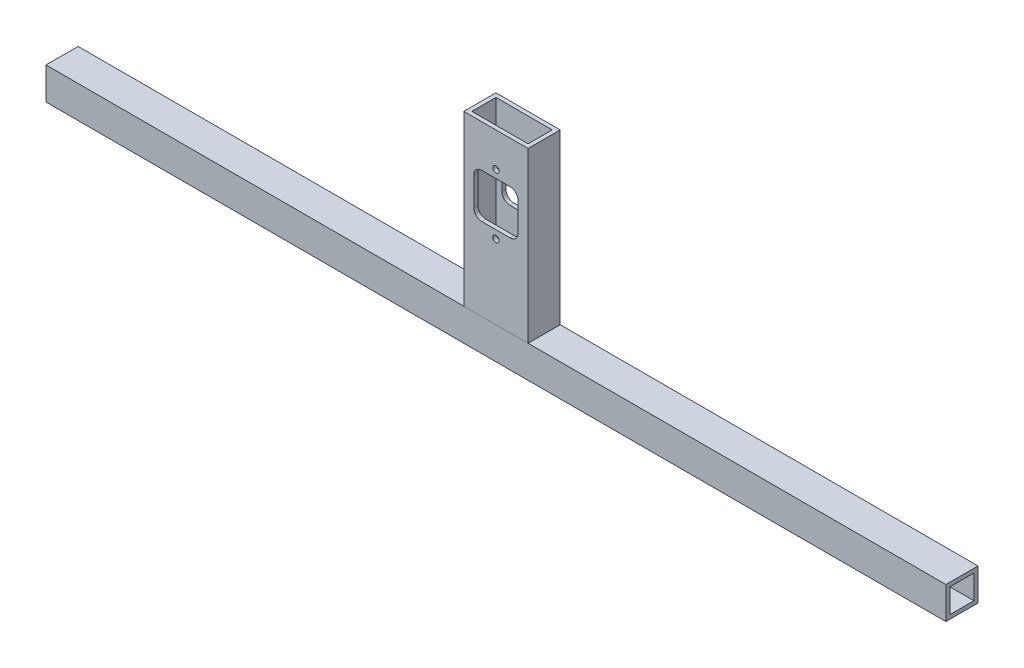
SolidWorks part; units mm, degrees
ref_plane "Alzado" through (0, 0, 0) normal (0, 0, 1) x (1, 0, 0)
ref_plane "Planta" through (0, 0, 0) normal (0, 1, 0) x (1, 0, 0)
ref_plane "Vista lateral" through (0, 0, 0) normal (1, 0, 0) x (0, 0, -1)
sketch "Croquis1" plane through (0, 0, 0) normal (0, 0, 1) x (1, 0, 0)
  line L0 (0, 0) -> (0, 68.072) construction
  line L5 (-355.6, -68.072) -> (355.6, -68.072)
  line L6 (-355.6, -68.072) -> (-355.6, 68.072)
  line L11 (-355.6, 68.072) -> (355.6, 68.072)
  line L13 (-355.6, -68.072) -> (355.6, 68.072) construction
  line L14 (-355.6, 68.072) -> (355.6, -68.072) construction
  line L15 (-355.6, 144.272) -> (-355.6, 17.272)
  line L20 (355.6, 68.072) -> (355.6, -68.072)
  line L21 (355.6, 17.272) -> (374.65, 17.272)
  line L22 (374.65, 17.272) -> (406.4, 17.272)
  line L23 (-374.65, 144.272) -> (-355.6, 144.272)
  line L24 (355.6, 17.272) -> (355.6, 68.072)
  line L25 (374.65, 144.272) -> (374.65, 17.272) construction
  line L26 (438.15, 49.022) -> (438.15, 112.522)
  line L27 (406.4, 144.272) -> (374.65, 144.272)
  line L28 (374.65, 144.272) -> (355.6, 144.272)
  line L29 (355.6, 144.272) -> (355.6, 17.272)
  line L30 (-406.4, 144.272) -> (-374.65, 144.272)
  line L31 (-438.15, 49.022) -> (-438.15, 112.522)
  line L32 (-355.6, 17.272) -> (-355.6, 68.072)
  line L33 (-374.65, 17.272) -> (-406.4, 17.272)
  line L34 (-355.6, 17.272) -> (-374.65, 17.272)
  arc A2 (406.4, 17.272) -> (438.15, 49.022) centre (406.4, 49.022) ccw
  arc A3 (438.15, 112.522) -> (406.4, 144.272) centre (406.4, 112.522) ccw
  arc A4 (-438.15, 112.522) -> (-406.4, 144.272) centre (-406.4, 112.522) cw
  arc A5 (-406.4, 17.272) -> (-438.15, 49.022) centre (-406.4, 49.022) cw
  point P0 (0, 0)
  point P29 (0, 0)
  dimension "D4" = 31.75
  dimension "D3" = 63.5
  dimension "D5" = 19.05
  dimension "D1" = 136.144
  dimension "D2" = 711.2
  dimension "D6" = 76.2
  dimension "D7" = 127
sketch "Croquis2" plane through (0, 0, 0) normal (0, 0, 1) x (1, 0, 0)
  line L0 (355.6, -68.072) -> (514.35, -68.072) construction
  line L1 (514.35, -68.072) -> (514.35, 620.903)
  line L3 (438.15, 49.022) -> (438.15, 112.522) construction
  line L4 (514.35, 620.903) -> (1193.1608, 1096.2115)
  line L5 (514.35, 620.903) -> (1193.1608, 620.903) construction
  point P6 (0, 0)
  dimension "D1" = 76.2
  dimension "D2" = 35
  dimension "D3" = 828.675
  dimension "D4" = 688.975
sketch "Croquis3" plane through (0, 0, 0) normal (0, 0, 1) x (1, 0, 0)
  line L0 (0, 68.072) -> (0, 176.022)
  line L1 (-355.6, 68.072) -> (355.6, 68.072) construction
  line L2 (0, 176.022) -> (-438.15, 176.022) construction
  line L3 (-438.15, 176.022) -> (-666.75, 176.022) construction
  line L4 (74.168, 201.422) -> (-438.15, 201.422)
  line L5 (74.168, 150.622) -> (-438.15, 150.622)
  line L6 (74.168, 150.622) -> (74.168, 201.422)
  line L7 (-438.15, 150.622) -> (-438.15, 201.422)
  line L8 (74.168, 176.022) -> (-438.15, 176.022) construction
  line L9 (-666.75, -23.622) -> (-355.6, -23.622) construction
  line L10 (-355.6, -68.072) -> (355.6, -68.072) construction
  line L15 (-473.6284, -45.0532) -> (-526.9684, 257.302)
  line L16 (-526.9684, 257.302) -> (-549.8284, 257.302)
  line L17 (-549.8284, 257.302) -> (-549.8284, -45.0532) construction
  line L18 (-549.8284, -45.0532) -> (-473.6284, -45.0532) construction
  line L20 (-355.6, -68.072) -> (-355.6, 68.072) construction
  line L23 (-612.8204, 5.7468) -> (-612.8204, -19.6532) construction
  line L26 (-562.0204, 5.7468) -> (-663.6204, 5.7468)
  line L29 (-562.0204, 5.7468) -> (-562.0204, -19.6532)
  line L32 (-562.0204, -19.6532) -> (-663.6204, -19.6532)
  line L35 (-663.6204, 5.7468) -> (-663.6204, -19.6532)
  line L36 (-612.8204, 346.2972) -> (-612.8204, 371.6972) construction
  line L37 (-663.6204, 346.2972) -> (-663.6204, 371.6972)
  line L38 (-562.0204, 371.6972) -> (-663.6204, 371.6972)
  line L39 (-562.0204, 346.2972) -> (-562.0204, 371.6972)
  line L40 (-562.0204, 346.2972) -> (-663.6204, 346.2972)
  line L41 (-57.6798, 122.9269) -> (186.5051, 573.3083)
  line L42 (-57.6798, 122.9269) -> (-13.0212, 98.7142)
  line L43 (186.5051, 573.3083) -> (231.1637, 549.0956)
  line L44 (-13.0212, 98.7142) -> (231.1637, 549.0956)
  line L45 (208.8344, 561.202) -> (-35.3505, 110.8205) construction
  line L46 (208.8344, 561.202) -> (316.2998, 759.4143) construction
  line L47 (417.5643, 588.9393) -> (439.8936, 576.8329)
  line L48 (417.5643, 588.9393) -> (465.9897, 678.2564)
  line L49 (439.8936, 576.8329) -> (488.319, 666.15)
  line L50 (465.9897, 678.2564) -> (488.319, 666.15)
  line L51 (-562.0204, 5.7468) -> (-438.15, 5.7468) construction
  line L52 (417.5643, 588.9393) -> (358.5243, 480.0441) construction
  line L53 (231.1637, 549.0956) -> (358.5243, 480.0441) construction
  line L54 (-438.15, 150.622) -> (-438.15, 5.7468) construction
  line L55 (316.2998, 759.4143) -> (488.319, 666.15) construction
  circle A0 centre (0, 176.022) radius 74.168
  arc A17 (-438.15, 49.022) -> (-406.4, 17.272) centre (-406.4, 49.022) ccw construction
  dimension "D1" = 148.336
  dimension "D11" = 50.8
  dimension "D2" = 228.6
  dimension "D5" = 44.45
  dimension "D6" = 25.4
  dimension "D7" = 101.6
  dimension "D8" = 22.86
  dimension "D9" = 76.2
  dimension "D10" = 23.0188
  dimension "D12" = 325.374
  dimension "D14" = 107.95
  dimension "D13" = 25.4
  dimension "D15" = 62.992
  dimension "D16" = 44.45
  dimension "D3" = 25.4
  dimension "D4" = 25.4
sketch "Croquis4" plane through (0, 0, 0) normal (0, 0, 1) x (1, 0, 0)
  line L0 (-355.6, 144.272) -> (-355.6, 17.272) construction
  line L1 (355.6, 68.072) -> (-355.6, 68.072)
  line L2 (355.6, 68.072) -> (355.6, 93.472)
  line L3 (355.6, 93.472) -> (-355.6, 93.472)
  line L4 (-355.6, 68.072) -> (-355.6, 93.472)
  line L5 (0, 226.822) -> (0, 93.472) construction
  line L6 (25.4, 93.472) -> (-25.4, 93.472)
  line L7 (25.4, 93.472) -> (25.4, 226.822)
  line L8 (25.4, 226.822) -> (-25.4, 226.822)
  line L9 (-25.4, 93.472) -> (-25.4, 226.822)
  line L10 (0, 68.072) -> (0, 176.022) construction
  line L11 (74.168, 201.422) -> (-438.15, 201.422) construction
  circle A0 centre (175.4299, 126.647) radius 30
  circle A1 centre (175.4299, 126.647) radius 7.62
  circle A2 centre (123.7021, 153.797) radius 50.8
  point P22 (117.7259, 152.1718)
  point P23 (123.0145, 153.797)
  point P25 (123.7021, 153.797)
  dimension "D1" = 60
  dimension "D2" = 15.24
  dimension "D4" = 101.6
  dimension "D3" = 25.4
  dimension "D5" = 50.8
  dimension "D6" = 25.4
  dimension "D7" = 3.175
  dimension "D8" = 9.525
sketch "Croquis5" plane through (0, 0, 0) normal (0, 0, 1) x (1, 0, 0)
  line L1 (-355.6, 93.472) -> (355.6, 93.472)
  line L2 (-355.6, 93.472) -> (-355.6, 68.072)
  line L3 (-355.6, 68.072) -> (355.6, 68.072)
  line L4 (355.6, 93.472) -> (355.6, 68.072)
extrude "Saliente-Extruir1" add sketch "Croquis5" against normal blind 25.4
sketch "Croquis6" plane through (0, 0, 0) normal (0, 0, 1) x (1, 0, 0)
  line L1 (-25.4, 226.822) -> (25.4, 226.822)
  line L2 (-25.4, 226.822) -> (-25.4, 93.472)
  line L3 (-25.4, 93.472) -> (25.4, 93.472)
  line L4 (25.4, 226.822) -> (25.4, 93.472)
extrude "Saliente-Extruir2" add sketch "Croquis6" against normal blind 25.4 separate body
shell "Vaciado1" thickness 3.175
shell "Vaciado2" thickness 3.175
sketch "Croquis7" plane through (0, 0, 0) normal (0, 0, 1) x (1, 0, 0)
  line L0 (0, 152.2095) -> (0, 199.8345) construction
  line L1 (-11.1506, 158.5214) -> (11.1506, 158.5214)
  line L2 (-17.5006, 164.8714) -> (-17.5006, 187.1726)
  line L3 (-11.1506, 193.5226) -> (11.1506, 193.5226)
  line L4 (17.5006, 164.8714) -> (17.5006, 187.1726)
  line L5 (-17.5006, 158.5214) -> (17.5006, 193.5226) construction
  line L6 (-17.5006, 193.5226) -> (17.5006, 158.5214) construction
  line L7 (0, 226.822) -> (0, 93.472) construction
  arc A0 (11.1506, 193.5226) -> (17.5006, 187.1726) centre (11.1506, 187.1726) cw
  arc A1 (11.1506, 158.5214) -> (17.5006, 164.8714) centre (11.1506, 164.8714) ccw
  arc A2 (-11.1506, 158.5214) -> (-17.5006, 164.8714) centre (-11.1506, 164.8714) cw
  arc A3 (-17.5006, 187.1726) -> (-11.1506, 193.5226) centre (-11.1506, 187.1726) cw
  circle A4 centre (0, 199.8345) radius 2.4892
  circle A5 centre (0, 152.2095) radius 2.4892
  point P0 (0, 176.022)
  point P23 (0, 176.022)
  dimension "D2" = 6.35
  dimension "D3" = 4.9784
  dimension "D1" = 35.0012
  dimension "D4" = 47.625
extrude "Cortar-Extruir1" cut sketch "Croquis7" against normal through all
ref_plane "Plano1" through (0, 0, -88.9) normal (0, 0, -1) x (-1, 0, 0)
equation "\"D4@Croquis4\"=80/20"
equation "\"D2@Croquis4\"=12/20"
equation "\"D1@Croquis7\"=\"tolerancia\" + 1.375"
equation "\"tolerancia\" = 0.003pulgadas"
equation "\"distancia entre perfiles\"= 5pulgadas / 2"
equation "\"D1@Plano1\"=\"distancia entre perfiles\""
